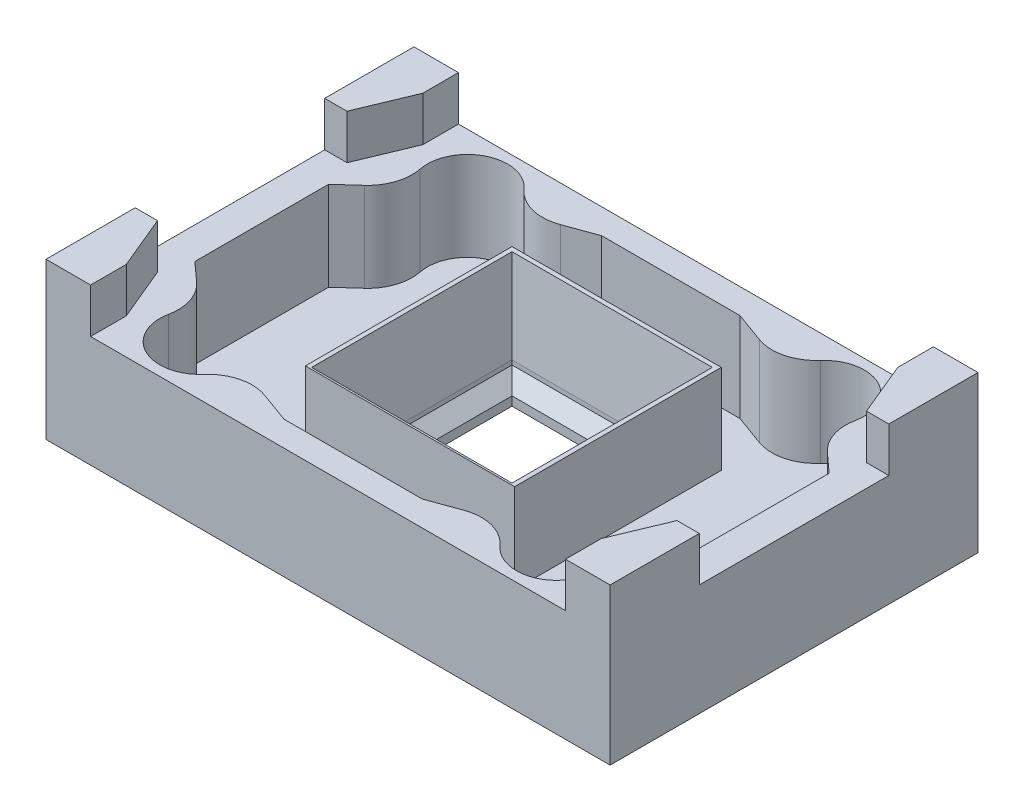
SolidWorks part; units mm, degrees
ref_plane "Спереди" through (0, 0, 0) normal (0, 0, 1) x (1, 0, 0)
ref_plane "Сверху" through (0, 0, 0) normal (0, 1, 0) x (1, 0, 0)
ref_plane "Справа" through (0, 0, 0) normal (1, 0, 0) x (0, 0, -1)
ref_plane "Плоскость4" through (0, 77.196, 0) normal (0, 1, 0) x (1, 0, 0)
sketch "Эскиз1" plane through (0, 77.196, 0) normal (0, 1, 0) x (1, 0, 0)
  line L0 (1.559, -48.2731) -> (1.559, -130.7731)
  line L1 (1.559, -130.7731) -> (128.059, -130.7731)
  line L2 (128.059, -130.7731) -> (128.059, -48.2731)
  line L3 (128.059, -48.2731) -> (128.059, -130.7731) construction
  line L4 (128.059, -48.2731) -> (1.559, -48.2731)
  line L5 (47.3449, -72.059) -> (47.3449, -106.9872)
  line L6 (47.3449, -106.9872) -> (82.2731, -106.9872)
  line L7 (82.2731, -106.9872) -> (82.2731, -72.059)
  line L8 (82.2731, -72.059) -> (82.2731, -106.9872) construction
  line L9 (47.3449, -72.059) -> (82.2731, -72.059) construction
  line L10 (82.2731, -72.059) -> (47.3449, -72.059)
  circle A0 centre (24.809, -59.5231) radius 2.1
  circle A1 centre (104.809, -59.5231) radius 2.1
  circle A2 centre (104.809, -119.5231) radius 1.9358
  circle A3 centre (24.809, -119.5231) radius 2.1
extrude "Бобышка-Вытянуть1" add sketch "Эскиз1" along normal blind 5
ref_plane "Плоскость5" through (0, 82.196, 0) normal (0, 1, 0) x (1, 0, 0)
sketch "Эскиз2" plane through (0, 82.196, 0) normal (0, 1, 0) x (1, 0, 0)
  line L4 (33.809, -59.5231) -> (49.309, -53.8981)
  line L8 (8.684, -74.5231) -> (8.684, -104.5231)
  line L12 (80.309, -53.8981) -> (49.309, -53.8981)
  line L16 (120.934, -104.5231) -> (120.934, -74.5231)
  line L20 (49.309, -125.1481) -> (80.309, -125.1481)
  line L21 (49.309, -125.1481) -> (33.809, -119.5231)
  line L22 (80.309, -125.1481) -> (95.809, -119.5231)
  line L27 (80.309, -53.8981) -> (95.809, -59.5231)
  line L30 (1.559, -48.2731) -> (1.559, -130.7731)
  line L33 (120.934, -104.5231) -> (111.267, -113.2546)
  line L34 (18.351, -113.2546) -> (8.684, -104.5231)
  line L35 (1.559, -130.7731) -> (128.059, -130.7731)
  line L36 (18.351, -65.7916) -> (8.684, -74.5231)
  line L37 (120.934, -74.5231) -> (111.267, -65.7916)
  line L38 (128.059, -130.7731) -> (128.059, -48.2731)
  line L39 (128.059, -48.2731) -> (1.559, -48.2731)
  circle A0 centre (24.809, -119.5231) radius 9
  circle A1 centre (104.809, -119.5231) radius 9
  circle A2 centre (104.809, -59.5231) radius 9
  circle A3 centre (24.809, -59.5231) radius 9
extrude "Бобышка-Вытянуть2" add sketch "Эскиз2" along normal blind 20 contours L38 L39 L30 L35 A3 L4 L12 L27 A2 L37 L16 L33 A1 L22 L20 L21 A0 L34 L8 L36
fillet "Скругление1" radius 10 8 edges at (95.809, 92.196, 119.5231) (111.267, 92.196, 113.2546) (33.809, 92.196, 119.5231) (18.351, 92.196, 113.2546) (18.351, 92.196, 65.7916) (33.809, 92.196, 59.5231) (95.809, 92.196, 59.5231) (111.267, 92.196, 65.7916)
chamfer "Фаска1" distance 3 angle 45 4 edges at (64.809, 82.196, 106.9872) (47.3449, 82.196, 89.5231) (82.2731, 82.196, 89.5231) (64.809, 82.196, 72.059)
sketch "Эскиз3" plane through (0, 82.196, 0) normal (0, 1, 0) x (1, 0, 0)
  line L0 (44.3449, -69.059) -> (44.3449, -109.9872)
  line L1 (44.3449, -109.9872) -> (85.2731, -109.9872)
  line L2 (85.2731, -109.9872) -> (85.2731, -69.059)
  line L3 (85.2731, -69.059) -> (44.3449, -69.059)
  line L4 (41.3449, -66.059) -> (88.2731, -66.059)
  line L11 (41.3449, -66.059) -> (41.3449, -112.3965)
  line L12 (41.3449, -112.3965) -> (88.2731, -112.3965)
  line L13 (88.2731, -66.059) -> (88.2731, -112.3965)
extrude "Бобышка-Вытянуть3" add sketch "Эскиз3" along normal blind 20
chamfer "Фаска2" distance 2 angle 84 4 edges at (64.809, 102.196, 109.9872) (44.3449, 102.196, 89.5231) (64.809, 102.196, 69.059) (85.2731, 102.196, 89.5231)
ref_plane "Плоскость6" through (0, 102.196, 0) normal (0, 1, 0) x (1, 0, 0)
sketch "Эскиз4" plane through (0, 102.196, 0) normal (0, 1, 0) x (1, 0, 0)
  line L0 (1.559, -48.2731) -> (1.559, -68.2731)
  line L1 (1.559, -48.2731) -> (1.559, -130.7731) construction
  line L2 (1.559, -68.2731) -> (6.559, -68.2731)
  line L3 (1.559, -48.2731) -> (11.559, -48.2731)
  line L4 (128.059, -48.2731) -> (1.559, -48.2731) construction
  line L5 (11.559, -48.2731) -> (11.559, -56.2731)
  line L6 (11.559, -56.2731) -> (6.559, -68.2731)
  line L7 (128.059, -48.2731) -> (118.059, -48.2731)
  line L8 (128.059, -130.7731) -> (118.059, -130.7731)
  line L9 (128.059, -130.7731) -> (128.059, -48.2731) construction
  line L10 (-8.25, -130.7731) -> (8.25, -130.7731) construction
  line L11 (1.559, -130.7731) -> (128.059, -130.7731) construction
  line L12 (1.559, -130.7731) -> (11.559, -130.7731)
  line L13 (128.059, -48.2731) -> (128.059, -68.2731)
  line L14 (128.059, -130.7731) -> (128.059, -110.7731)
  line L15 (1.559, -130.7731) -> (1.559, -110.7731)
  line L16 (1.559, -110.7731) -> (6.559, -110.7731)
  line L17 (11.559, -130.7731) -> (11.559, -122.7731)
  line L18 (11.559, -122.7731) -> (6.559, -110.7731)
  line L19 (118.059, -130.7731) -> (118.059, -122.7731)
  line L20 (128.059, -110.7731) -> (123.059, -110.7731)
  line L21 (123.059, -110.7731) -> (118.059, -122.7731)
  line L22 (128.059, -68.2731) -> (123.059, -68.2731)
  line L23 (118.059, -48.2731) -> (118.059, -56.2731)
  line L24 (118.059, -56.2731) -> (123.059, -68.2731)
extrude "Бобышка-Вытянуть4" add sketch "Эскиз4" along normal blind 10
